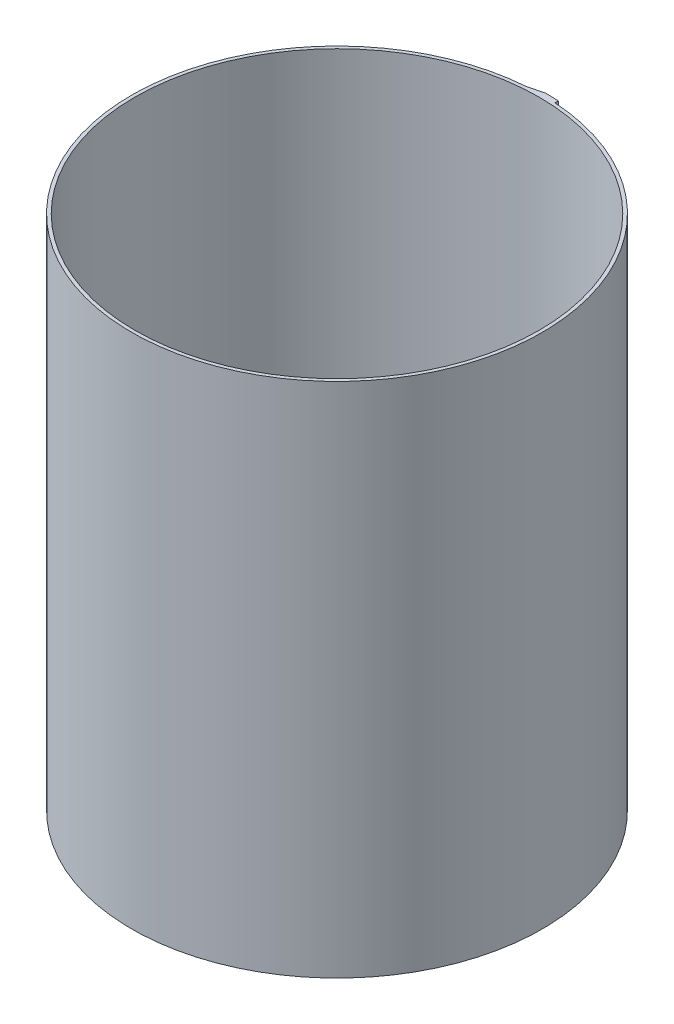
SolidWorks part; units mm, degrees
material "Brass"
ref_plane "Front Plane" through (0, 0, 0) normal (0, 0, 1) x (1, 0, 0)
ref_plane "Top Plane" through (0, 0, 0) normal (0, 1, 0) x (1, 0, 0)
ref_plane "Right Plane" through (0, 0, 0) normal (1, 0, 0) x (0, 0, -1)
sketch "Sketch1" plane through (0, 0, 0) normal (0, 1, 0) x (1, 0, 0)
  line L0 (0, 63) -> (0, 64.02)
  line L1 (4.0321, 63.8929) -> (3.9679, 62.8749)
  line L2 (0, 64.02) -> (-4.8521, 62.8129)
  circle A0 centre (0, 0) radius 61.98
  circle A1 centre (0, 0) radius 63
  arc A2 (0, 64.02) -> (4.0321, 63.8929) centre (0, 0) cw
  point P11 (4, 63.3839)
  dimension "D2" = 126
  dimension "D1" = 1.02
  dimension "D3" = 1.02
  dimension "D4" = 4
  dimension "D5" = 5
extrude "Boss-Extrude1" add sketch "Sketch1" along normal blind 158.49 contours A2 L0 A1 L1 | A1 L0 L2 | A1 A0
equation "\"D3@Sketch1\"=\"D1@Sketch1\""
